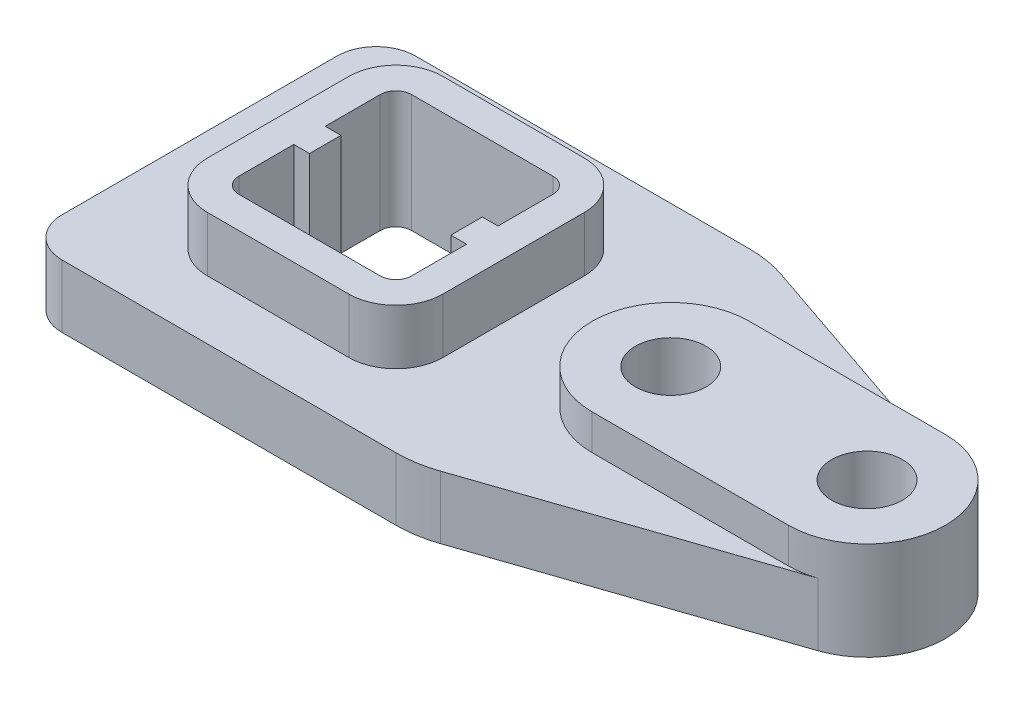
SolidWorks part; units mm, degrees
material "普通碳钢"
ref_plane "前视基准面" through (0, 0, 0) normal (0, 0, 1) x (1, 0, 0)
ref_plane "上视基准面" through (0, 0, 0) normal (0, 1, 0) x (1, 0, 0)
ref_plane "右视基准面" through (0, 0, 0) normal (1, 0, 0) x (0, 0, -1)
sketch "草图1" plane through (0, 0, 0) normal (0, 1, 0) x (1, 0, 0)
  line L1 (0, 45) -> (100, 45)
  line L2 (0, 45) -> (0, -45)
  line L3 (0, -45) -> (100, -45)
  line L4 (100, 45) -> (100, -45)
extrude "凸台-拉伸1" add sketch "草图1" along normal blind 16
fillet "圆角1" radius 10 2 edges at (0, 8, -45) (0, 8, 45)
sketch "草图4" plane through (0, 0, 0) normal (0, 1, 0) x (1, 0, 0)
  line L1 (20, 30) -> (80, 30)
  line L2 (20, 30) -> (20, -30)
  line L3 (20, -30) -> (80, -30)
  line L4 (80, 30) -> (80, -30)
extrude "凸台-拉伸2" add sketch "草图4" along normal blind 30
fillet "圆角3" radius 12 4 edges at (20, 23, 30) (20, 23, -30) (80, 23, 30) (80, 23, -30)
sketch "草图5" plane through (0, 0, 0) normal (0, 1, 0) x (1, 0, 0)
  line L0 (28, -4) -> (28, -22)
  line L1 (28, 22) -> (72, 22)
  line L2 (28, 22) -> (28, 4)
  line L3 (28, -22) -> (72, -22)
  line L4 (72, 22) -> (72, 4)
  line L5 (28, 4) -> (32, 4)
  line L7 (28, -4) -> (32, -4)
  line L8 (32, 4) -> (32, -4)
  line L9 (72, 4) -> (68, 4)
  line L11 (72, -4) -> (68, -4)
  line L12 (68, 4) -> (68, -4)
  line L13 (72, -4) -> (72, -22)
extrude "切除-拉伸1" cut sketch "草图5" along normal blind 46
fillet "圆角4" radius 4 4 edges at (28, 15, -22) (28, 15, 22) (72, 15, 22) (72, 15, -22)
sketch "草图9" plane through (0, 0, 0) normal (0, 1, 0) x (1, 0, 0)
  line L0 (120, 20) -> (171.0386, 19.973)
  line L1 (170, -20) -> (120, -20)
  line L2 (100, 45) -> (176.4548, 18.9297)
  line L3 (100, -45) -> (176.4548, -18.9297)
  line L4 (100, 45) -> (100, -45)
  circle A0 centre (120, 0) radius 20
  circle A1 centre (170, 0) radius 20
extrude "凸台-拉伸4" add sketch "草图9" along normal blind 16 contours A1 L2 L4 A0 L0 | A1 L1 A0 L4 L3
sketch "草图10" plane through (0, 0, 0) normal (0, 1, 0) x (1, 0, 0)
  line L0 (120, 20) -> (170, 20)
  line L1 (170, -20) -> (120, -20)
  arc A0 (120, 20) -> (120, -20) centre (120, 0) ccw
  arc A1 (170, -20) -> (170, 20) centre (170, 0) ccw
  circle A2 centre (120, 0) radius 9
  circle A3 centre (170, 0) radius 9
extrude "凸台-拉伸5" add sketch "草图10" along normal blind 25
fillet "圆角6" radius 30 2 edges at (100, 8, -45) (100, 8, 45)
